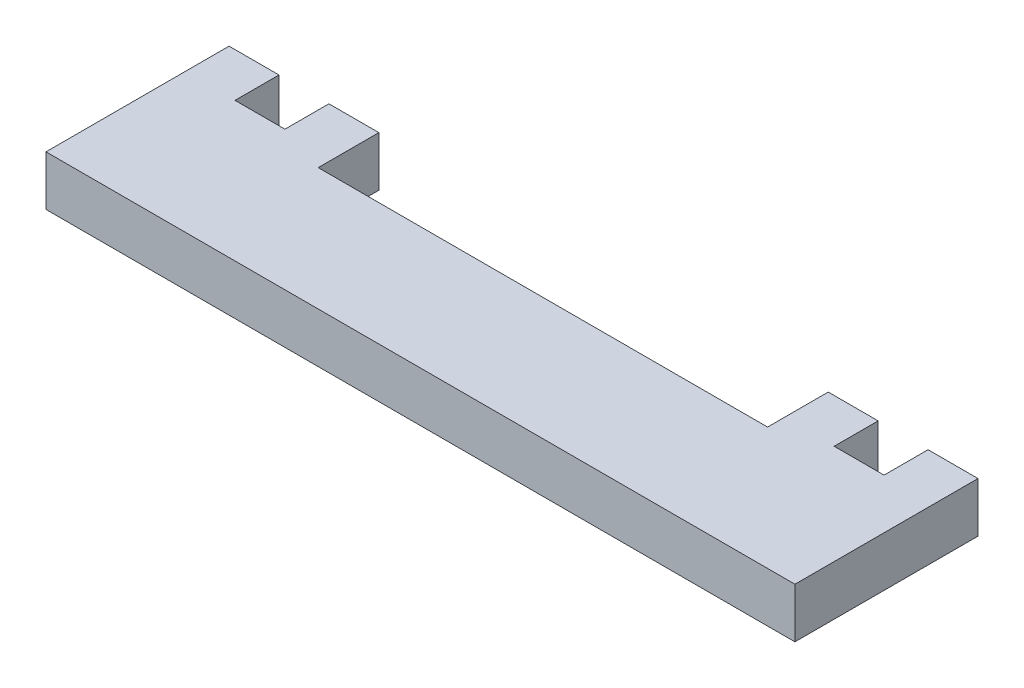
SolidWorks part; units mm, degrees
ref_plane "Front Plane" through (0, 0, 0) normal (0, 0, 1) x (1, 0, 0)
ref_plane "Top Plane" through (0, 0, 0) normal (0, 1, 0) x (1, 0, 0)
ref_plane "Right Plane" through (0, 0, 0) normal (1, 0, 0) x (0, 0, -1)
sketch "Sketch1" plane through (0, 0, 0) normal (0, 1, 0) x (1, 0, 0)
  line L0 (0, 4.8564) -> (0, -4) construction
  line L5 (-22.5, -4) -> (22.5, -4)
  line L6 (-22.5, -4) -> (-22.5, 4)
  line L7 (-19.5, 4.3564) -> (-16.5, 4.3564)
  line L8 (22.5, -4) -> (22.5, 4)
  line L9 (-22.5, -4) -> (22.5, 4) construction
  line L10 (-22.5, 4) -> (22.5, -4) construction
  line L12 (-22.5, 4) -> (-22.5, 7)
  line L13 (-22.5, 7) -> (-19.5, 7)
  line L14 (-19.5, 4.3564) -> (-19.5, 7)
  line L16 (-16.5, 4.3564) -> (-16.5, 7)
  line L17 (-16.5, 7) -> (-13.5, 7)
  line L18 (-13.5, 6.3564) -> (-13.5, 7)
  line L19 (13.5, 6.3564) -> (13.5, 7)
  line L20 (16.5, 7) -> (13.5, 7)
  line L21 (16.5, 4.3564) -> (16.5, 7)
  line L23 (19.5, 4.3564) -> (19.5, 7)
  line L24 (22.5, 7) -> (19.5, 7)
  line L25 (22.5, 4) -> (22.5, 7)
  line L28 (16.5, 4.3564) -> (19.5, 4.3564)
  line L36 (-13.5, 6.3564) -> (-13.5, 3.3564)
  line L37 (-13.5, 3.3564) -> (13.5, 3.3564)
  line L38 (13.5, 6.3564) -> (13.5, 3.3564)
  point P0 (0, 0)
  dimension "D1" = 45
  dimension "D2" = 8
  dimension "D3" = 3
  dimension "D4" = 3
  dimension "D5" = 3
  dimension "D6" = 27
  dimension "D7" = 3
  dimension "D8" = 1
extrude "Boss-Extrude1" add sketch "Sketch1" along normal blind 3 contours L19 L38 L37 L36 L18 L17 L16 L7 L14 L13 L12 L6 L5 L8 L25 L24 L23 L28 L21 L20
